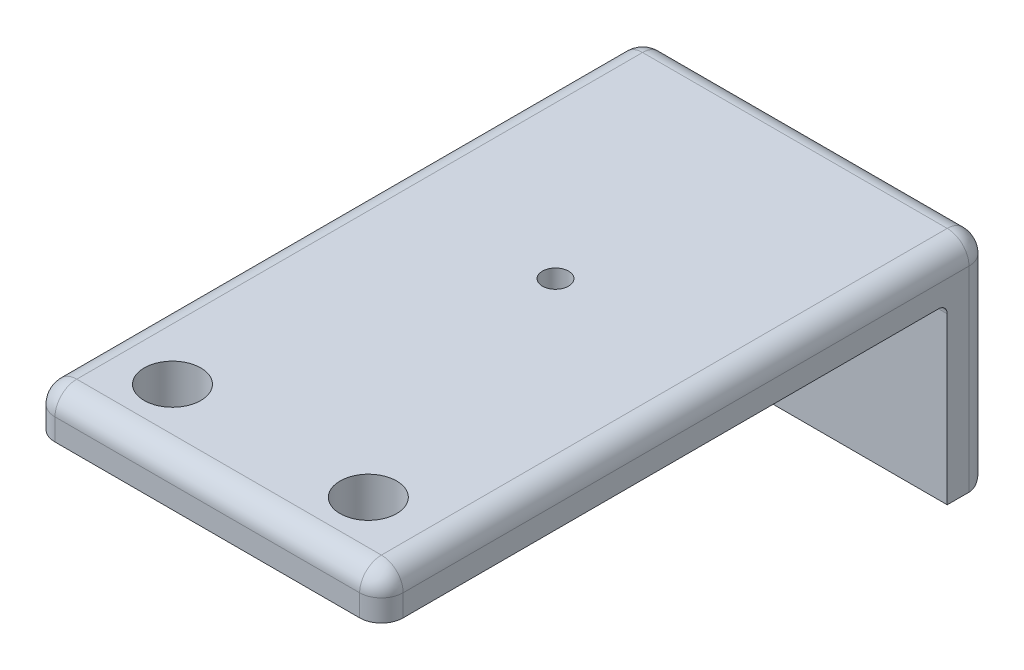
SolidWorks part; units mm, degrees
ref_plane "Front Plane" through (0, 0, 0) normal (0, 0, 1) x (1, 0, 0)
ref_plane "Top Plane" through (0, 0, 0) normal (0, 1, 0) x (1, 0, 0)
ref_plane "Right Plane" through (0, 0, 0) normal (1, 0, 0) x (0, 0, -1)
sketch "Sketch1" plane through (0, 0, 0) normal (1, 0, 0) x (0, 0, -1)
  line L0 (0, 0) -> (130, 0)
  line L1 (130, 0) -> (130, -40)
  line L2 (130, -40) -> (140, -40)
  line L3 (140, -40) -> (140, 10)
  line L4 (140, 10) -> (0, 10)
  line L5 (0, 10) -> (0, 0)
  dimension "D1" = 130
  dimension "D2" = 10
  dimension "D3" = 10
  dimension "D4" = 40
extrude "Boss-Extrude1" add sketch "Sketch1" along normal blind 80
sketch "Sketch2" plane through (0, 0, 0) normal (0, -1, 0) x (1, 0, 0)
  line L0 (0, 0) -> (0, -130) construction
  line L1 (80, -130) -> (0, -130) construction
  circle A0 centre (17, -15) radius 6.5
  circle A1 centre (62, -15) radius 6.5
  dimension "D1" = 13
  dimension "D2" = 13
  dimension "D3" = 45
  dimension "D4" = 17
  dimension "D5" = 115
extrude "Cut-Extrude1" cut sketch "Sketch2" against normal through all
sketch "Sketch3" plane through (0, 0, 0) normal (0, -1, 0) x (1, 0, 0)
  line L0 (80, -130) -> (0, -130) construction
  line L1 (80, -130) -> (0, -130) construction
  circle A0 centre (40, -80) radius 33
  point P4 (40, -130)
  dimension "D1" = 66
  dimension "D2" = 50
extrude "Cut-Extrude2" cut sketch "Sketch3" against normal blind 5
fillet "Fillet1" radius 2 2 edges at (40, 0, -113) (40, 5, -113)
sketch "Sketch4" plane through (0, 0, -130) normal (0, 0, 1) x (1, 0, 0)
  line L0 (80, 0) -> (0, 0) construction
  circle A0 centre (40, -28) radius 6.5
  point P4 (40, 0)
  dimension "D1" = 13
  dimension "D2" = 28
extrude "Cut-Extrude3" cut sketch "Sketch4" against normal through all
fillet "Fillet2" radius 5 9 edges at (40, -40, -140) (80, -15, -140) (0, -15, -140) (40, 10, -140) (80, 5, 0) (80, 10, -70) (40, 10, 0) (0, 5, 0) (0, 10, -70)
fillet "Fillet3" radius 2 1 edges at (40, 0, -130)
sketch "Sketch5" plane through (0, 5, 0) normal (0, -1, 0) x (1, 0, 0)
  circle A0 centre (40, -80) radius 3
  dimension "D1" = 6
extrude "Cut-Extrude4" cut sketch "Sketch5" against normal through all
